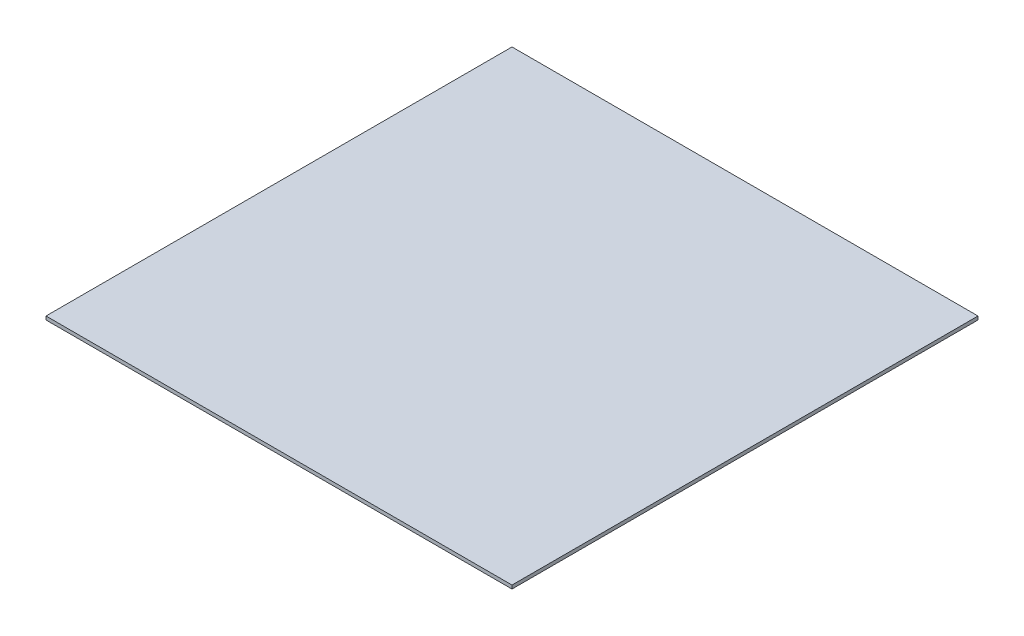
SolidWorks part; units mm, degrees
material "Custom Plastic"
ref_plane "Front Plane" through (0, 0, 0) normal (0, 0, 1) x (1, 0, 0)
ref_plane "Top Plane" through (0, 0, 0) normal (0, 1, 0) x (1, 0, 0)
ref_plane "Right Plane" through (0, 0, 0) normal (1, 0, 0) x (0, 0, -1)
sketch "Sketch1" plane through (0, 0, 0) normal (0, 1, 0) x (1, 0, 0)
  line L1 (-106.75, 106.75) -> (106.75, 106.75)
  line L2 (-106.75, 106.75) -> (-106.75, -106.75)
  line L3 (-106.75, -106.75) -> (106.75, -106.75)
  line L4 (106.75, 106.75) -> (106.75, -106.75)
  line L5 (-106.75, 106.75) -> (106.75, -106.75) construction
  line L6 (-106.75, -106.75) -> (106.75, 106.75) construction
  point P0 (0, 0)
  dimension "D1" = 213.5
  dimension "D2" = 213.5
extrude "Boss-Extrude1" add sketch "Sketch1" along normal blind 1.6
